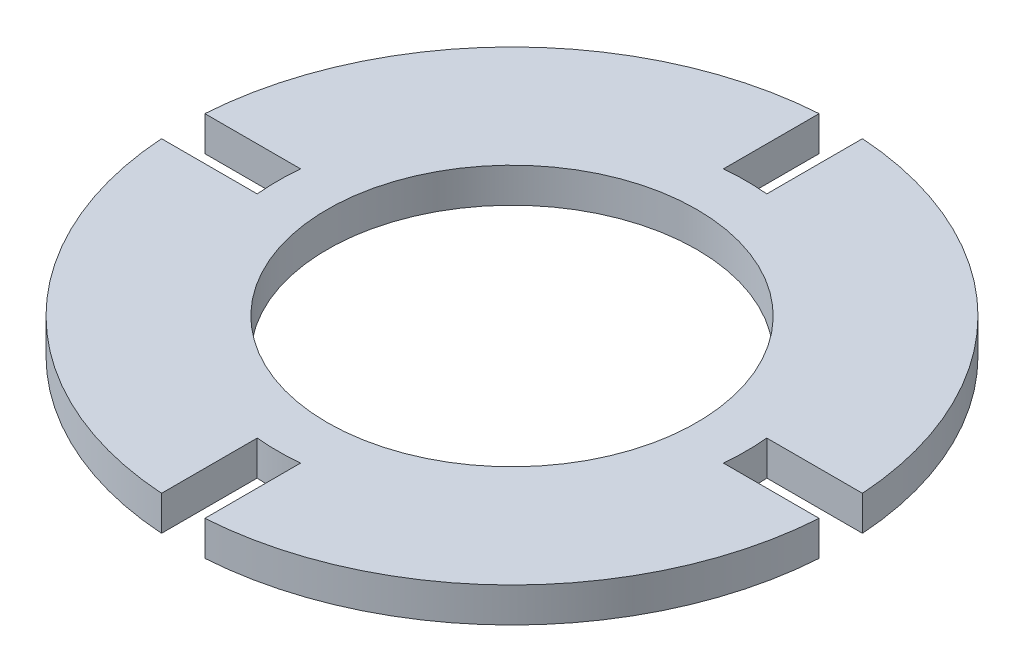
SolidWorks part; units mm, degrees
ref_plane "Front Plane" through (0, 0, 0) normal (0, 0, 1) x (1, 0, 0)
ref_plane "Top Plane" through (0, 0, 0) normal (0, 1, 0) x (1, 0, 0)
ref_plane "Right Plane" through (0, 0, 0) normal (1, 0, 0) x (0, 0, -1)
sketch "Sketch1" plane through (0, 0, 0) normal (0, 1, 0) x (1, 0, 0)
  line L0 (34.1427, 3.175) -> (48.1554, 3.175)
  line L2 (-3.175, 48.1554) -> (-3.175, 34.1427)
  line L4 (3.175, 48.1554) -> (3.175, 34.1427)
  line L5 (-48.1554, 3.175) -> (-34.1427, 3.175)
  line L7 (-48.1554, -3.175) -> (-34.1427, -3.175)
  line L10 (-3.175, -34.1427) -> (-3.175, -48.1554)
  line L11 (3.175, -34.1427) -> (3.175, -48.1554)
  line L13 (34.1427, -3.175) -> (48.1554, -3.175)
  circle A0 centre (0, 0) radius 48.26
  arc A2 (-34.1427, 3.175) -> (-34.1427, -3.175) centre (0, 0) ccw
  arc A3 (-3.175, -34.1427) -> (3.175, -34.1427) centre (0, 0) ccw
  arc A5 (34.1427, -3.175) -> (34.1427, 3.175) centre (0, 0) ccw
  arc A6 (3.175, 34.1427) -> (-3.175, 34.1427) centre (0, 0) ccw
  dimension "D1" = 96.52
  dimension "D2" = 6.35
  dimension "D4" = 68.58
extrude "Boss-Extrude1" add sketch "Sketch1" along normal blind 5.08 contours L4 A6 L2 A0 L5 A2 L7 L10 A3 L11 L13 A5 L0
sketch "Sketch2" plane through (0, 5.08, 0) normal (0, 1, 0) x (1, 0, 0)
  circle A0 centre (0, 0) radius 27.051
  dimension "D1" = 54.102
extrude "Cut-Extrude1" cut sketch "Sketch2" against normal through all
